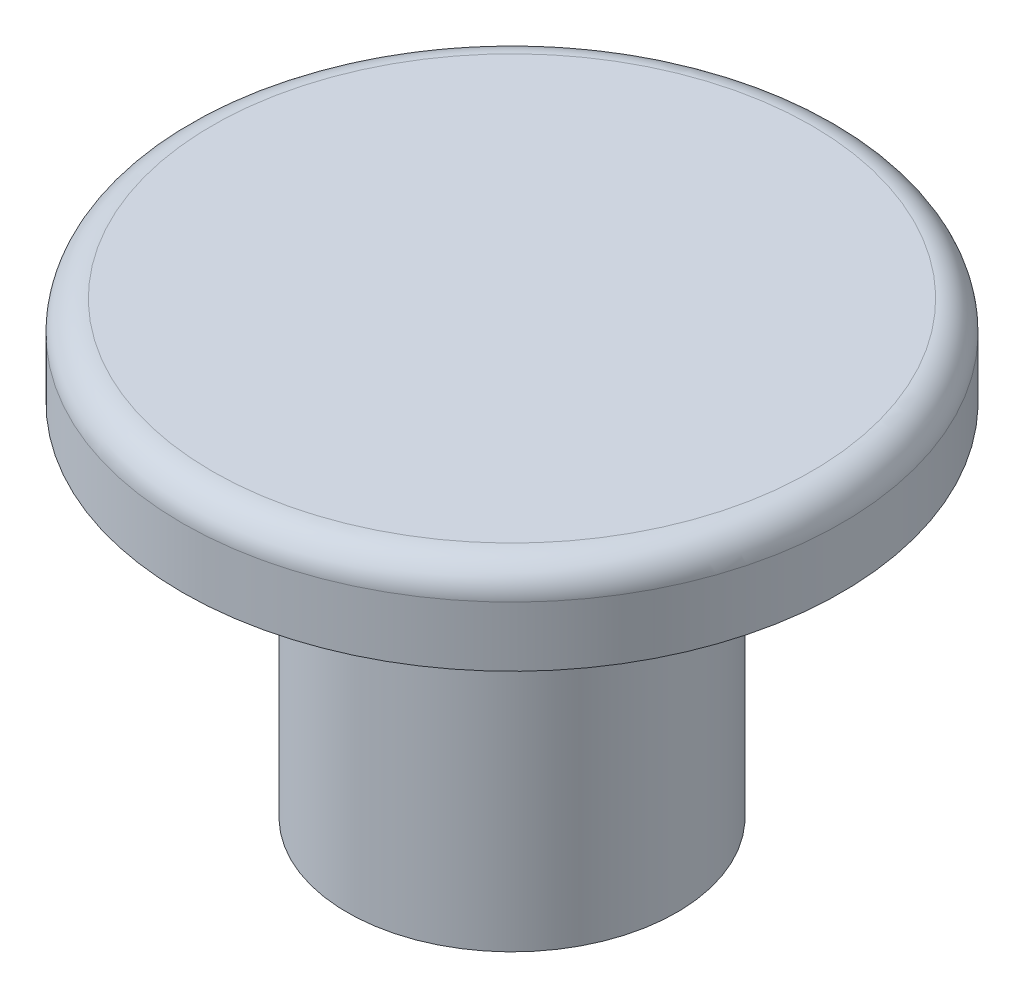
SolidWorks part; units mm, degrees
ref_plane "Front Plane" through (0, 0, 0) normal (0, 0, 1) x (1, 0, 0)
ref_plane "Top Plane" through (0, 0, 0) normal (0, 1, 0) x (1, 0, 0)
ref_plane "Right Plane" through (0, 0, 0) normal (1, 0, 0) x (0, 0, -1)
sketch "Sketch1" plane through (0, 0, 0) normal (0, 1, 0) x (1, 0, 0)
  circle A0 centre (0, 0) radius 11
  dimension "D1" = 22
extrude "Boss-Extrude1" add sketch "Sketch1" along normal blind 3
sketch "Sketch2" plane through (0, 0, 0) normal (0, -1, 0) x (1, 0, 0)
  circle A0 centre (0, 0) radius 5.5
  dimension "D1" = 11
extrude "Boss-Extrude2" add sketch "Sketch2" along normal blind 12
fillet "Fillet1" radius 1 1 edges at (0, 3, 11)
